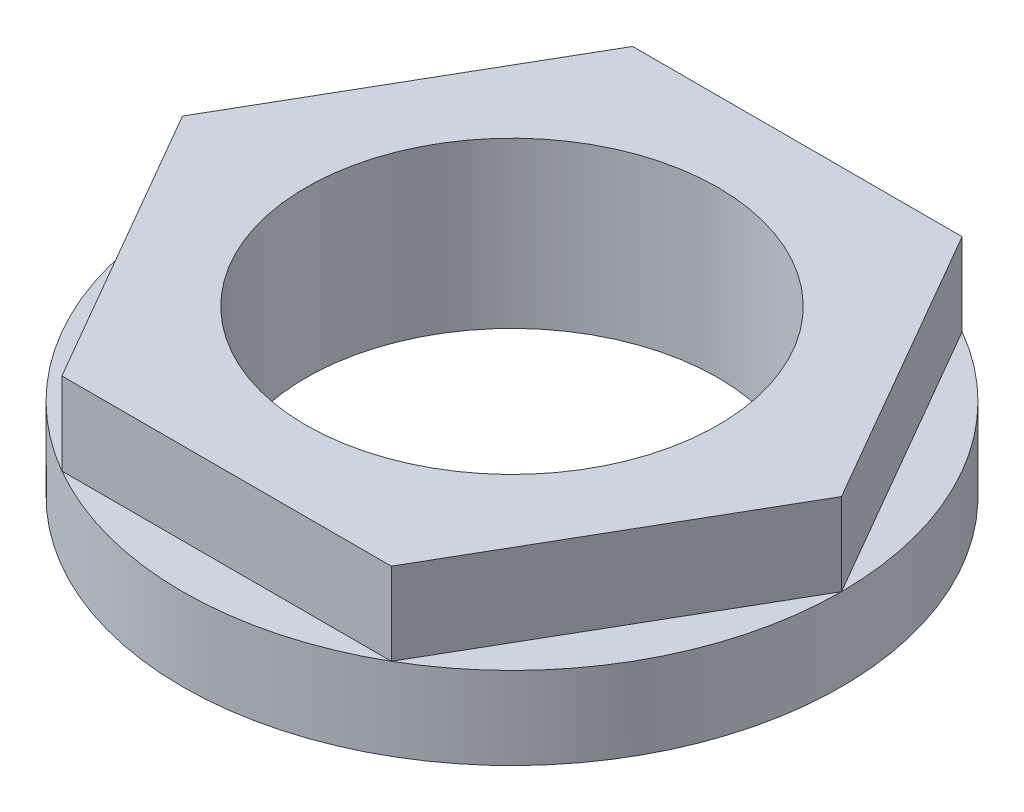
SolidWorks part; units mm, degrees
material "PMMA"
ref_plane "Front Plane" through (0, 0, 0) normal (0, 0, 1) x (1, 0, 0)
ref_plane "Top Plane" through (0, 0, 0) normal (0, 1, 0) x (1, 0, 0)
ref_plane "Right Plane" through (0, 0, 0) normal (1, 0, 0) x (0, 0, -1)
sketch "Sketch1" plane through (0, 0, 0) normal (0, 1, 0) x (1, 0, 0)
  circle A0 centre (0, 0) radius 7.5
  circle A1 centre (0, 0) radius 12
  dimension "D1" = 15
  dimension "D2" = 24
extrude "Boss-Extrude1" add sketch "Sketch1" along normal blind 3
cosmetic thread "Cosmetic Thread1" parameters "D1"=5, "D2"=18
sketch "Sketch2" plane through (0, 3, 0) normal (0, 1, 0) x (1, 0, 0)
  line L0 (0, 12.9485) -> (0, -12.6898) construction
  line L1 (12, 0) -> (6, 10.3923)
  line L2 (6, 10.3923) -> (-6, 10.3923)
  line L3 (-6, 10.3923) -> (-12, 0)
  line L4 (-12, 0) -> (-6, -10.3923)
  line L5 (-6, -10.3923) -> (6, -10.3923)
  line L6 (6, -10.3923) -> (12, 0)
  line L7 (-15.8969, 0) -> (13.2777, 0) construction
  circle A0 centre (0, 0) radius 7.5
  circle A1 centre (0, 0) radius 10.3923 construction
  dimension "D1" = 15
  dimension "D2" = 20.7846
extrude "Boss-Extrude2" add sketch "Sketch2" along normal blind 3
